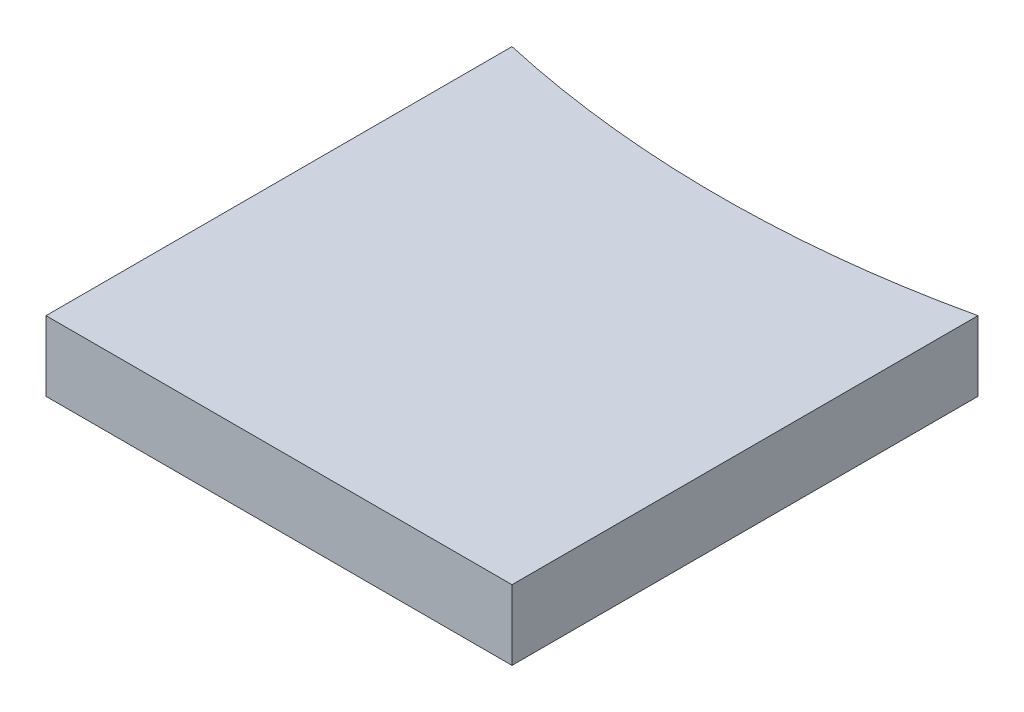
SolidWorks part; units mm, degrees
ref_plane "Front Plane" through (0, 0, 0) normal (0, 0, 1) x (1, 0, 0)
ref_plane "Top Plane" through (0, 0, 0) normal (0, 1, 0) x (1, 0, 0)
ref_plane "Right Plane" through (0, 0, 0) normal (1, 0, 0) x (0, 0, -1)
sketch "Sketch1" plane through (0, 0, 0) normal (0, 1, 0) x (1, 0, 0)
  line L0 (0, 0) -> (20, 0)
  line L1 (20, 0) -> (20, 20)
  line L2 (0, 0) -> (0, 20)
  arc A0 (0, 20) -> (20, 20) centre (10, 64.4102) ccw
  dimension "D1" = 20
  dimension "D2" = 20
extrude "Boss-Extrude1" add sketch "Sketch1" along normal blind 3
